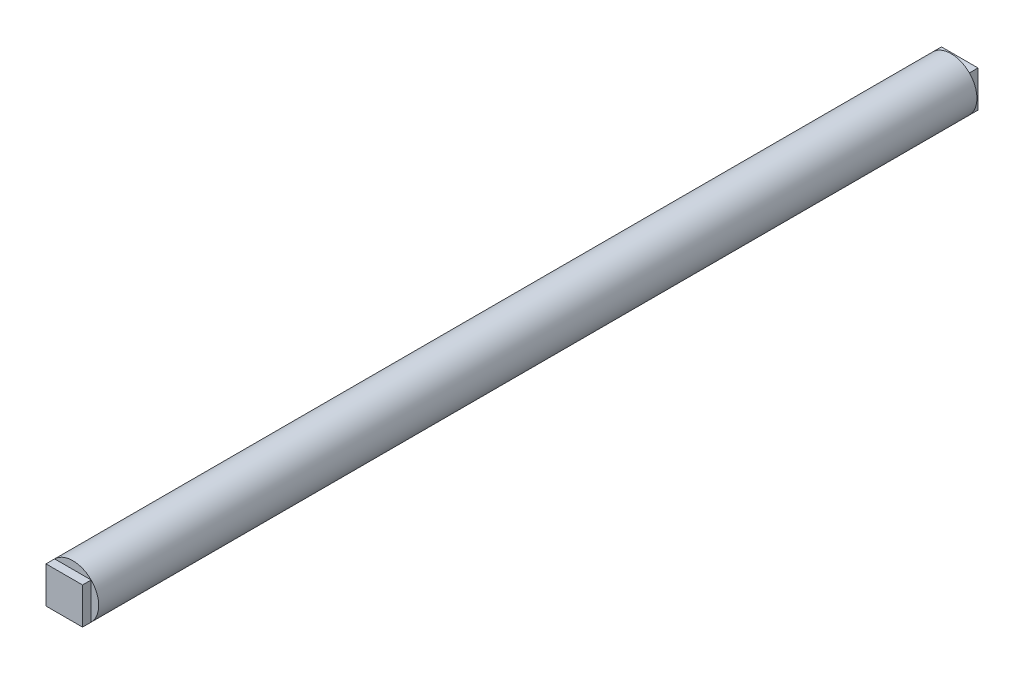
SolidWorks part; units mm, degrees
ref_plane "Front Plane" through (0, 0, 0) normal (0, 0, 1) x (1, 0, 0)
ref_plane "Top Plane" through (0, 0, 0) normal (0, 1, 0) x (1, 0, 0)
ref_plane "Right Plane" through (0, 0, 0) normal (1, 0, 0) x (0, 0, -1)
sketch "Main bar cross section" plane through (0, 0, 0) normal (0, 0, 1) x (1, 0, 0)
  circle A0 centre (0, 0) radius 3
  dimension "D1" = 6
extrude "Boss-Extrude1" add sketch "Main bar cross section" along normal blind 102
sketch "Sketch2" plane through (0, 0, 0) normal (0, 0, -1) x (-1, 0, 0)
  line L1 (2.1213, -2.1213) -> (2.1213, 2.1213)
  line L2 (2.1213, 2.1213) -> (-2.1213, 2.1213)
  line L3 (-2.1213, 2.1213) -> (-2.1213, -2.1213)
  line L4 (-2.1213, -2.1213) -> (2.1213, -2.1213)
  circle A0 centre (0, 0) radius 2.1213 construction
  circle A1 centre (0, 0) radius 3 construction
extrude "Boss-Extrude2" add sketch "Sketch2" along normal blind 1
sketch "Sketch3" plane through (0, 0, 102) normal (0, 0, 1) x (1, 0, 0)
  line L1 (-2.12, 2.1226) -> (2.12, 2.1226)
  line L2 (-2.12, 2.1226) -> (-2.12, -2.1226)
  line L3 (-2.12, -2.1226) -> (2.12, -2.1226)
  line L4 (2.12, 2.1226) -> (2.12, -2.1226)
  line L5 (-2.12, 2.1226) -> (2.12, -2.1226) construction
  line L6 (-2.12, -2.1226) -> (2.12, 2.1226) construction
  circle A0 centre (0, 0) radius 3 construction
  point P0 (0, 0)
  dimension "D1" = 4.24
extrude "Boss-Extrude3" add sketch "Sketch3" along normal blind 1
